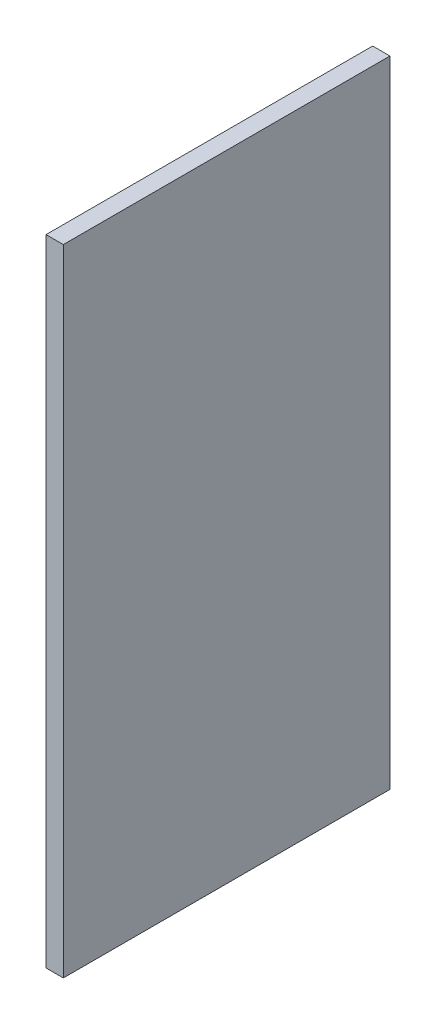
SolidWorks part; units mm, degrees
ref_plane "Alzado" through (0, 0, 0) normal (0, 0, 1) x (1, 0, 0)
ref_plane "Planta" through (0, 0, 0) normal (0, 1, 0) x (1, 0, 0)
ref_plane "Vista lateral" through (0, 0, 0) normal (1, 0, 0) x (0, 0, -1)
sketch "Croquis2" plane through (0, 0, 0) normal (1, 0, 0) x (0, 0, -1)
  line L1 (-90, -175) -> (90, -175)
  line L2 (-90, -175) -> (-90, 175)
  line L3 (-90, 175) -> (90, 175)
  line L4 (90, -175) -> (90, 175)
  line L5 (-90, -175) -> (90, 175) construction
  line L6 (-90, 175) -> (90, -175) construction
  point P0 (0, 0)
  point P6 (0, 0)
  point P7 (90, -66.409)
  point P8 (0, 0)
  dimension "D1" = 180
  dimension "D2" = 350
extrude "Saliente-Extruir1" add sketch "Croquis2" along normal mid plane 9.525
